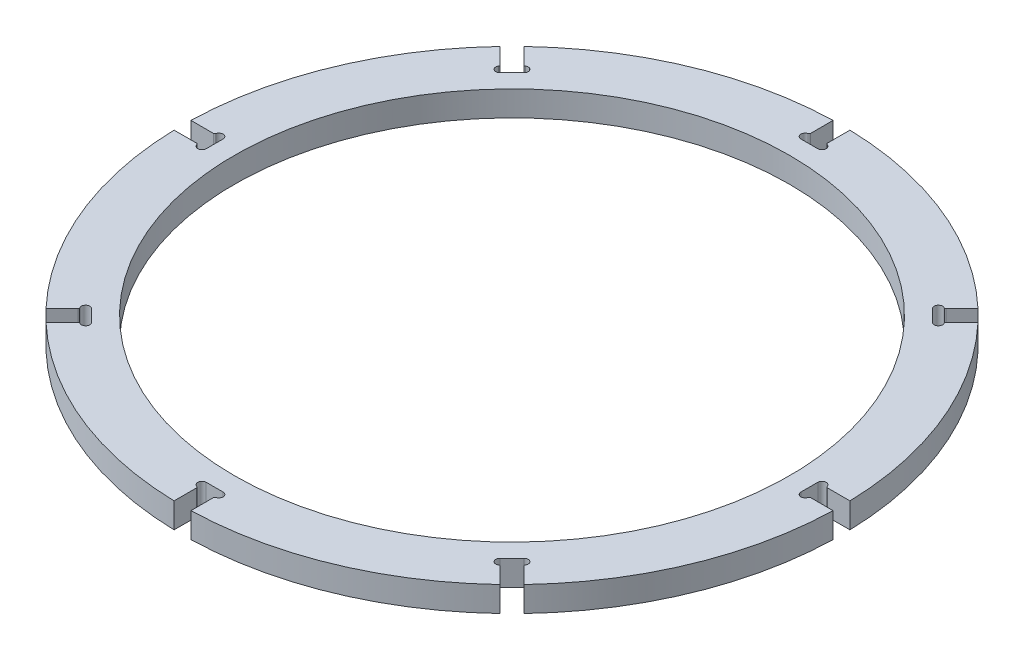
SolidWorks part; units mm, degrees
ref_plane "Front Plane" through (0, 0, 0) normal (0, 0, 1) x (1, 0, 0)
ref_plane "Top Plane" through (0, 0, 0) normal (0, 1, 0) x (1, 0, 0)
ref_plane "Right Plane" through (0, 0, 0) normal (1, 0, 0) x (0, 0, -1)
sketch "Sketch1" plane through (0, 0, 0) normal (0, 1, 0) x (1, 0, 0)
  circle A0 centre (0, 0) radius 210.5
  circle A1 centre (0, 0) radius 250
  dimension "D1" = 421
  dimension "D2" = 500
extrude "Boss-Extrude1" add sketch "Sketch1" along normal blind 19.05
sketch "Sketch2" plane through (0, 19.05, 0) normal (0, 1, 0) x (1, 0, 0)
  line L0 (0, 0) -> (0, 210.5) construction
  line L1 (0, 210.5) -> (0, 250) construction
  line L2 (0, 210.5) -> (0, 225.5) construction
  line L3 (0, 225.5) -> (0, 250) construction
  line L4 (6.4, 225.5) -> (6.4, 250) construction
  line L5 (-6.4, 225.5) -> (-6.4, 250) construction
  line L6 (6.4, 225.5) -> (-6.4, 225.5)
  line L7 (6.4, 250) -> (-6.4, 250)
  line L8 (-6.4, 250) -> (-6.4, 231.9)
  line L9 (6.4, 250) -> (6.4, 231.9)
  circle A0 centre (0, 0) radius 210.5 construction
  circle A1 centre (0, 0) radius 250 construction
  arc A2 (-6.4, 231.9) -> (-6.4, 225.5) centre (-6.4, 228.7) ccw
  arc A3 (6.4, 225.5) -> (6.4, 231.9) centre (6.4, 228.7) ccw
  dimension "D4" = 6.4
  dimension "D1" = 225.5
  dimension "D2" = 6.4
  dimension "D3" = 6.4
extrude "Cut-Extrude1" cut sketch "Sketch2" against normal through all
fillet "Fillet1" radius 1 2 edges at (6.4, 9.525, -231.9) (-6.4, 9.525, -231.9)
pattern_circular "CirPattern1" count 8 over 360 about axis through (0, 0, 0) along (0, 1, 0) of "Fillet1", "Cut-Extrude1"
